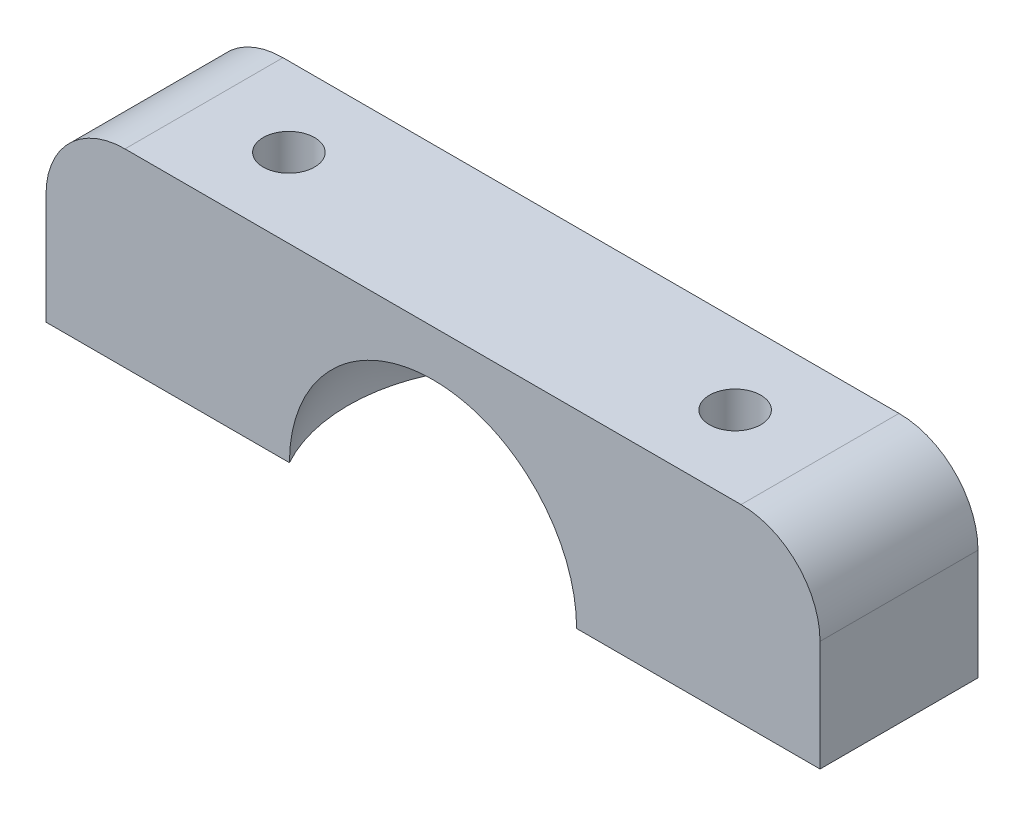
SolidWorks part; units mm, degrees
ref_plane "前视基准面" through (0, 0, 0) normal (0, 0, 1) x (1, 0, 0)
ref_plane "上视基准面" through (0, 0, 0) normal (0, 1, 0) x (1, 0, 0)
ref_plane "右视基准面" through (0, 0, 0) normal (1, 0, 0) x (0, 0, -1)
other "Configuration Table"
sketch "草图1" plane through (0, 0, 0) normal (0, 0, 1) x (1, 0, 0)
  line L0 (-3.4641, 0) -> (-9.8, 0)
  line L1 (-9.8, 0) -> (-9.8, -4.8)
  line L2 (-9.8, -4.8) -> (9.8, -4.8)
  line L3 (9.8, -4.8) -> (9.8, 0)
  line L4 (9.8, 0) -> (3.4641, 0)
  line L6 (0, 0) -> (0, -7.44) construction
  line L7 (0, -2) -> (-3.4641, 0) construction
  line L8 (-3.4641, 0) -> (3.4641, 0)
  point P11 (9.8, -2.4)
  dimension "D3" = 60
  dimension "D1" = 19.6
  dimension "D2" = 4.8
extrude "凸台-拉伸1" add sketch "草图1" along normal mid plane 4
sketch "草图2" plane through (0, 0, 0) normal (0, 1, 0) x (1, 0, 0)
  line L0 (-5.65, 0) -> (5.65, 0)
  line L1 (-9.8, -2) -> (-9.8, 2) construction
  line L2 (9.8, -2) -> (9.8, 2) construction
  dimension "D1" = 4.15
  dimension "D2" = 4.15
hole_wizard "孔1" positions "草图3" profile "草图4" legacy end condition up to next
sketch "草图3" plane through (0, 0, 0) normal (0, 1, 0) x (1, 0, 0)
  point P0 (-5.65, 0)
  point P3 (5.65, 0)
sketch "草图4" plane through (-5.65, 0, 0) normal (1, 0, 0) x (0, 0, 1)
  line L0 (0, 0) -> (0, 4.8)
  line L1 (0, 4.8) -> (0.65, 4.8)
  line L2 (0.65, 4.8) -> (0.65, 0)
  line L3 (0.65, 0) -> (0, 0)
  line L4 (0, 110) -> (0, -10) construction
  dimension "直径" = 1.3
  dimension "深度" = 4.8
sketch "草图5" plane through (0, 0, 0) normal (0, 0, 1) x (1, 0, 0)
  line L0 (0, -4.8) -> (4.15, -4.8)
  line L1 (-9.8, -4.8) -> (9.8, -4.8) construction
  line L2 (0, 0) -> (0, -3.4843) construction
  line L4 (0, -0.65) -> (0, -8.95)
  circle A0 centre (0, -4.8) radius 4.15
  dimension "D1" = 8.3
  dimension "D2" = 90
revolve "切除-旋转1" cut sketch "草图5" angle 360 about L2
fillet "圆角1" radius 2 2 edges at (-9.8, 0, 0) (9.8, 0, 0)
